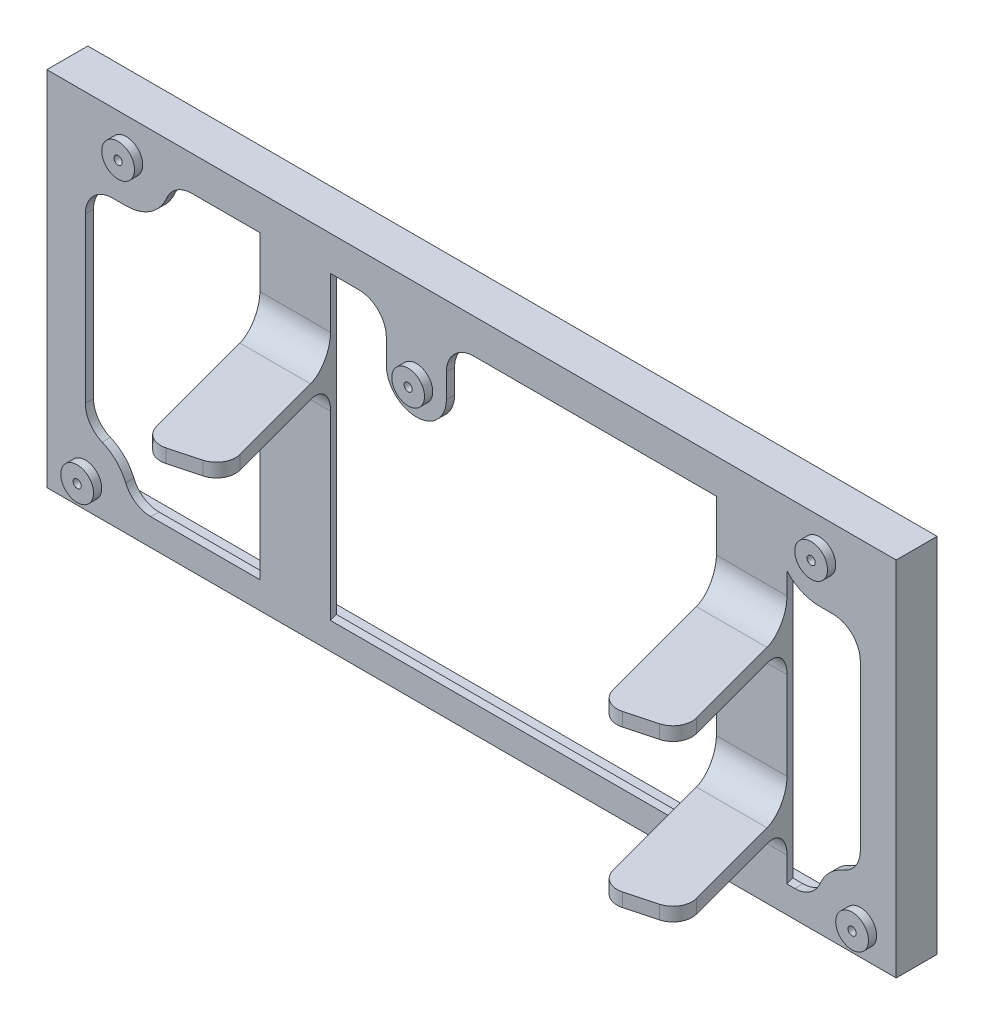
SolidWorks part; units mm, degrees
ref_plane "Front Plane" through (0, 0, 0) normal (0, 0, 1) x (1, 0, 0)
ref_plane "Top Plane" through (0, 0, 0) normal (0, 1, 0) x (1, 0, 0)
ref_plane "Right Plane" through (0, 0, 0) normal (1, 0, 0) x (0, 0, -1)
sketch "Sketch1" plane through (0, 0, 0) normal (0, 0, 1) x (1, 0, 0)
  circle A0 centre (0, 0) radius 1.5
  circle A1 centre (-106.24, 18.83) radius 1.5
  circle A2 centre (147.61, 18.83) radius 1.5
  circle A3 centre (-121.24, -91.25) radius 1.5
  circle A4 centre (162.61, -91.25) radius 1.5
  circle A5 centre (0, 0) radius 6
  circle A6 centre (-106.24, 18.83) radius 6
  circle A7 centre (147.61, 18.83) radius 6
  circle A8 centre (-121.24, -91.25) radius 6
  circle A9 centre (162.61, -91.25) radius 6
  dimension "D1" = 3
  dimension "D4" = 18.83
  dimension "D5" = 162.61
  dimension "D2" = 147.61
  dimension "D3" = 106.24
  dimension "D6" = 121.24
  dimension "D7" = 91.25
  dimension "D8" = 4.5
extrude "Display screw pattern" add sketch "Sketch1" along normal blind 3
sketch "Sketch2" plane through (0, 0, 0) normal (0, 0, -1) x (-1, 0, 0)
  line L0 (135.34, 31.53) -> (135.34, -101.07)
  line L1 (133.84, 30.03) -> (-174.26, 30.03) construction
  line L2 (133.84, 30.03) -> (133.84, -99.57) construction
  line L3 (133.84, -99.57) -> (-174.26, -99.57) construction
  line L4 (-174.26, 30.03) -> (-174.26, -99.57) construction
  line L5 (135.34, -101.07) -> (-175.76, -101.07)
  line L6 (-175.76, 31.53) -> (-175.76, -101.07)
  line L7 (135.34, 31.53) -> (-175.76, 31.53)
  circle A2 centre (106.24, 18.83) radius 4
  circle A3 centre (106.24, 18.83) radius 4
  circle A8 centre (0, 0) radius 4
  circle A9 centre (0, 0) radius 4
  circle A11 centre (121.24, -91.25) radius 4
  circle A12 centre (121.24, -91.25) radius 4
  circle A14 centre (-147.61, 18.83) radius 4
  circle A15 centre (-147.61, 18.83) radius 4
  circle A17 centre (-162.61, -91.25) radius 4
  circle A18 centre (-162.61, -91.25) radius 4
  dimension "D6" = 11.2
  dimension "D7" = 26.65
  dimension "D8" = 8.32
  dimension "D9" = 27.6
  dimension "D1" = 2
  dimension "D2" = 2
  dimension "D3" = 2
  dimension "D4" = 2
  dimension "D5" = 2
  dimension "D10" = 1.5
extrude "Display backplane" add sketch "Sketch2" along normal blind 3
sketch "Sketch3" plane through (0, 0, 0) normal (0, 0, 1) x (1, 0, 0)
  line L1 (162.61, -7.17) -> (162.61, -67.25)
  line L2 (138.61, -91.25) -> (-97.24, -91.25)
  line L3 (-121.24, -67.25) -> (-121.24, -7.17)
  line L5 (-82.24, 18.83) -> (-21, 18.83)
  line L6 (11, 8.83) -> (11, 0)
  line L7 (-11, 0) -> (-11, 8.83)
  line L8 (21, 18.83) -> (123.61, 18.83)
  line L9 (147.61, 2.83) -> (152.61, 2.83)
  line L10 (-106.24, 2.83) -> (-111.24, 2.83)
  arc A0 (123.61, 18.83) -> (132.8408, 12.6762) centre (123.61, 8.83) cw
  arc A1 (152.61, 2.83) -> (162.61, -7.17) centre (152.61, -7.17) cw
  arc A2 (162.61, -67.25) -> (156.4562, -76.4808) centre (152.61, -67.25) cw
  circle A4 centre (-121.24, -91.25) radius 16
  arc A5 (-106.4708, -85.0962) -> (-115.0862, -76.4808) centre (-121.24, -91.25) ccw
  arc A6 (138.61, -91.25) -> (147.8408, -85.0962) centre (138.61, -81.25) ccw
  circle A7 centre (162.61, -91.25) radius 16
  arc A8 (156.4562, -76.4808) -> (147.8408, -85.0962) centre (162.61, -91.25) ccw
  arc A9 (-97.24, -91.25) -> (-106.4708, -85.0962) centre (-97.24, -81.25) cw
  arc A10 (-121.24, -67.25) -> (-115.0862, -76.4808) centre (-111.24, -67.25) ccw
  arc A11 (-111.24, 2.83) -> (-121.24, -7.17) centre (-111.24, -7.17) ccw
  arc A12 (-82.24, 18.83) -> (-91.4708, 12.6762) centre (-82.24, 8.83) ccw
  circle A15 centre (0, 0) radius 11
  arc A16 (-11, 0) -> (11, 0) centre (0, 0) ccw
  arc A29 (21, 18.83) -> (11, 8.83) centre (21, 8.83) ccw
  arc A30 (-11, 8.83) -> (-21, 18.83) centre (-21, 8.83) ccw
  circle A36 centre (-106.24, 18.83) radius 16
  arc A37 (-106.24, 2.83) -> (-91.4708, 12.6762) centre (-106.24, 18.83) ccw
  circle A38 centre (147.61, 18.83) radius 16
  arc A39 (132.8408, 12.6762) -> (147.61, 2.83) centre (147.61, 18.83) ccw
  point P29 (131.61, 18.83)
  point P43 (162.61, -75.25)
  point P47 (146.61, -91.25)
  point P50 (-105.24, -91.25)
  point P53 (-121.24, -75.25)
  point P58 (-90.24, 18.83)
  dimension "D6" = 10
  dimension "D7" = 10
  dimension "D1" = 10
  dimension "D2" = 5
  dimension "D3" = 10
  dimension "D4" = 10
  dimension "D5" = 10
extrude "Backplane weight reduction" cut sketch "Sketch3" against normal through all both and the other way through all
sketch "Sketch4" plane through (0, 0, -3) normal (0, 0, -1) x (-1, 0, 0)
  line L12 (134.34, 30.53) -> (-174.76, 30.53)
  line L13 (-174.76, 30.53) -> (-174.76, -100.07)
  line L14 (-174.76, -100.07) -> (134.34, -100.07)
  line L15 (134.34, -100.07) -> (134.34, 30.53)
  line L16 (135.34, 31.53) -> (-175.76, 31.53)
  line L17 (-175.76, 31.53) -> (-175.76, -101.07)
  line L18 (-175.76, -101.07) -> (135.34, -101.07)
  line L19 (135.34, -101.07) -> (135.34, 31.53)
  line L20 (135.34, 31.53) -> (-175.76, 31.53)
  line L21 (-175.76, 31.53) -> (-175.76, -101.07)
  line L22 (-175.76, -101.07) -> (135.34, -101.07)
  line L23 (135.34, -101.07) -> (135.34, 31.53)
  dimension "D1" = 0
  dimension "D2" = 1
extrude "Display outside craddle" add sketch "Sketch4" along normal blind 12
ref_plane "Plane at center of radio mounts" through (0, -43.47, 0) normal (0, 1, 0) x (1, 0, 0)
ref_plane "Top radio mount plane" through (0, -14.845, 0) normal (0, 1, 0) x (1, 0, 0)
ref_plane "Bottom radio mount plane" through (0, -72.095, 0) normal (0, 1, 0) x (1, 0, 0)
sketch "Sketch5" plane through (0, -72.095, 0) normal (0, 1, 0) x (1, 0, 0)
  line L0 (-135.34, 0) -> (175.76, 0) construction
  line L2 (134.9562, 3) -> (147.9092, -45.3413)
  line L3 (142.9594, -53.9145) -> (132.3342, -56.7615)
  line L4 (123.761, -51.8117) -> (109.0742, 3)
  line L6 (105.3842, 0) -> (135.76, 0) construction
  line L12 (-32.241, 3) -> (-19.2879, -45.3413) construction
  line L13 (-24.2377, -53.9145) -> (-34.8629, -56.7615) construction
  line L14 (130.5225, -50) -> (133.537, -40) construction
  line L15 (133.537, -40) -> (141.1477, -47.153) construction
  line L17 (134.9562, 3) -> (109.0742, 3)
  line L18 (175.76, 15) -> (175.76, 0) construction
  line L19 (-43.4361, -51.8117) -> (-58.1229, 3) construction
  line L20 (-32.241, 3) -> (-58.1229, 3) construction
  line L22 (-36.6746, -50) -> (-33.6601, -40) construction
  line L23 (-33.6601, -40) -> (-26.0494, -47.153) construction
  line L24 (-61.8129, 0) -> (-31.4371, 0) construction
  arc A0 (132.3342, -56.7615) -> (123.761, -51.8117) centre (130.5225, -50) cw
  arc A1 (147.9092, -45.3413) -> (142.9594, -53.9145) centre (141.1477, -47.153) cw
  circle A10 centre (130.5225, -50) radius 1.5 construction
  circle A11 centre (141.1477, -47.153) radius 1.5 construction
  circle A13 centre (133.537, -40) radius 1.5 construction
  arc A14 (-34.8629, -56.7615) -> (-43.4361, -51.8117) centre (-36.6746, -50) cw construction
  arc A15 (-19.2879, -45.3413) -> (-24.2377, -53.9145) centre (-26.0494, -47.153) cw construction
  circle A16 centre (-36.6746, -50) radius 1.5 construction
  circle A17 centre (-26.0494, -47.153) radius 1.5 construction
  circle A18 centre (-33.6601, -40) radius 1.5 construction
  point P8 (125.5727, -58.5732)
  point P11 (149.7209, -52.1027)
  dimension "D3" = 7
  dimension "D1" = 75
  dimension "D2" = 25
  dimension "D4" = 3
  dimension "D5" = 50
  dimension "D7" = 186.5
  dimension "D10" = 40
  dimension "D6" = 2
extrude "Bottom radio mount tabs" add sketch "Sketch5" along normal blind 5 separate body
sketch "Sketch7" plane through (0, -14.845, 0) normal (0, 1, 0) x (1, 0, 0)
  line L2 (-32.241, 3) -> (-19.2879, -45.3413) construction
  line L30 (-32.241, 3) -> (-58.1229, 3) construction
  line L31 (-43.4361, -51.8117) -> (-58.1229, 3) construction
  line L32 (-24.2377, -53.9145) -> (-34.8629, -56.7615) construction
  line L33 (-32.241, 3) -> (-19.2879, -45.3413)
  line L34 (-32.241, 3) -> (-58.1229, 3)
  line L35 (-43.4361, -51.8117) -> (-58.1229, 3)
  line L36 (-24.2377, -53.9145) -> (-34.8629, -56.7615)
  line L41 (132.3342, -56.7615) -> (142.9594, -53.9145)
  line L42 (147.9092, -45.3413) -> (134.9562, 3)
  line L43 (134.9562, 3) -> (109.0742, 3)
  line L44 (109.0742, 3) -> (123.761, -51.8117)
  line L45 (132.3342, -56.7615) -> (142.9594, -53.9145)
  line L46 (147.9092, -45.3413) -> (134.9562, 3)
  line L47 (134.9562, 3) -> (109.0742, 3)
  line L48 (109.0742, 3) -> (123.761, -51.8117)
  arc A16 (-43.4361, -51.8117) -> (-34.8629, -56.7615) centre (-36.6746, -50) ccw construction
  arc A17 (-24.2377, -53.9145) -> (-19.2879, -45.3413) centre (-26.0494, -47.153) ccw construction
  arc A18 (-43.4361, -51.8117) -> (-34.8629, -56.7615) centre (-36.6746, -50) ccw
  arc A42 (-24.2377, -53.9145) -> (-19.2879, -45.3413) centre (-26.0494, -47.153) ccw
  arc A45 (123.761, -51.8117) -> (132.3342, -56.7615) centre (130.5225, -50) ccw
  arc A46 (142.9594, -53.9145) -> (147.9092, -45.3413) centre (141.1477, -47.153) ccw
  arc A47 (123.761, -51.8117) -> (132.3342, -56.7615) centre (130.5225, -50) ccw
  arc A48 (142.9594, -53.9145) -> (147.9092, -45.3413) centre (141.1477, -47.153) ccw
  dimension "D1" = 0
extrude "Top radio mount tabs" add sketch "Sketch7" along normal blind 5 separate body
sketch "Sketch9" plane through (0, -9.845, 0) normal (0, 1, 0) x (1, 0, 0)
  line L0 (109.0742, 3) -> (134.9562, 3)
  line L9 (134.9562, 3) -> (135.76, 0)
  line L10 (147.9092, -45.3413) -> (134.9562, 3) construction
  line L11 (135.76, 0) -> (109.8781, 0)
  line L12 (109.0742, 3) -> (123.761, -51.8117) construction
  line L13 (109.8781, 0) -> (109.0742, 3)
  line L14 (-58.1229, 3) -> (-32.241, 3)
  line L15 (-32.241, 3) -> (-31.4371, 0)
  line L16 (-19.2879, -45.3413) -> (-32.241, 3) construction
  line L17 (-31.4371, 0) -> (-57.319, 0)
  line L18 (-58.1229, 3) -> (-43.4361, -51.8117) construction
  line L19 (-57.319, 0) -> (-58.1229, 3)
extrude "Boss-Extrude6" add sketch "Sketch9" along normal up to next
sketch "Sketch10" plane through (0, -67.095, 0) normal (0, 1, 0) x (1, 0, 0)
  line L0 (109.0742, 3) -> (109.8781, 0)
  line L5 (109.0742, 3) -> (123.761, -51.8117) construction
  line L6 (109.8781, 0) -> (135.76, 0)
  line L7 (147.9092, -45.3413) -> (134.9562, 3) construction
  line L8 (135.76, 0) -> (134.9562, 3)
  line L9 (134.9562, 3) -> (109.0742, 3)
extrude "Boss-Extrude7" add sketch "Sketch10" along normal up to next
sketch "Sketch11" plane through (0, -72.095, 0) normal (0, -1, 0) x (1, 0, 0)
  line L10 (134.9562, -3) -> (109.0742, -3)
  line L11 (109.0742, -3) -> (109.8781, 0)
  line L12 (109.0742, -3) -> (123.761, 51.8117) construction
  line L13 (109.8781, 0) -> (135.76, 0)
  line L14 (147.9092, 45.3413) -> (134.9562, -3) construction
  line L15 (135.76, 0) -> (134.9562, -3)
extrude "Boss-Extrude8" add sketch "Sketch11" along normal up to next
sketch "Sketch12" plane through (0, -14.845, 0) normal (0, -1, 0) x (1, 0, 0)
  line L8 (-32.241, -3) -> (-58.1229, -3)
  line L9 (-58.1229, -3) -> (-57.319, 0)
  line L10 (-58.1229, -3) -> (-43.4361, 51.8117) construction
  line L11 (-57.319, 0) -> (-31.4371, 0)
  line L12 (-19.2879, 45.3413) -> (-32.241, -3) construction
  line L13 (-31.4371, 0) -> (-32.241, -3)
extrude "Boss-Extrude9" add sketch "Sketch12" along normal up to next
fillet "Tab fillets 10mm" radius 10 6 edges at (122.819, -14.845, 0) (122.819, -9.845, 0) (122.819, -67.095, 0) (122.819, -72.095, 0) (-44.3781, -14.845, 0) (-44.3781, -9.845, 0)
